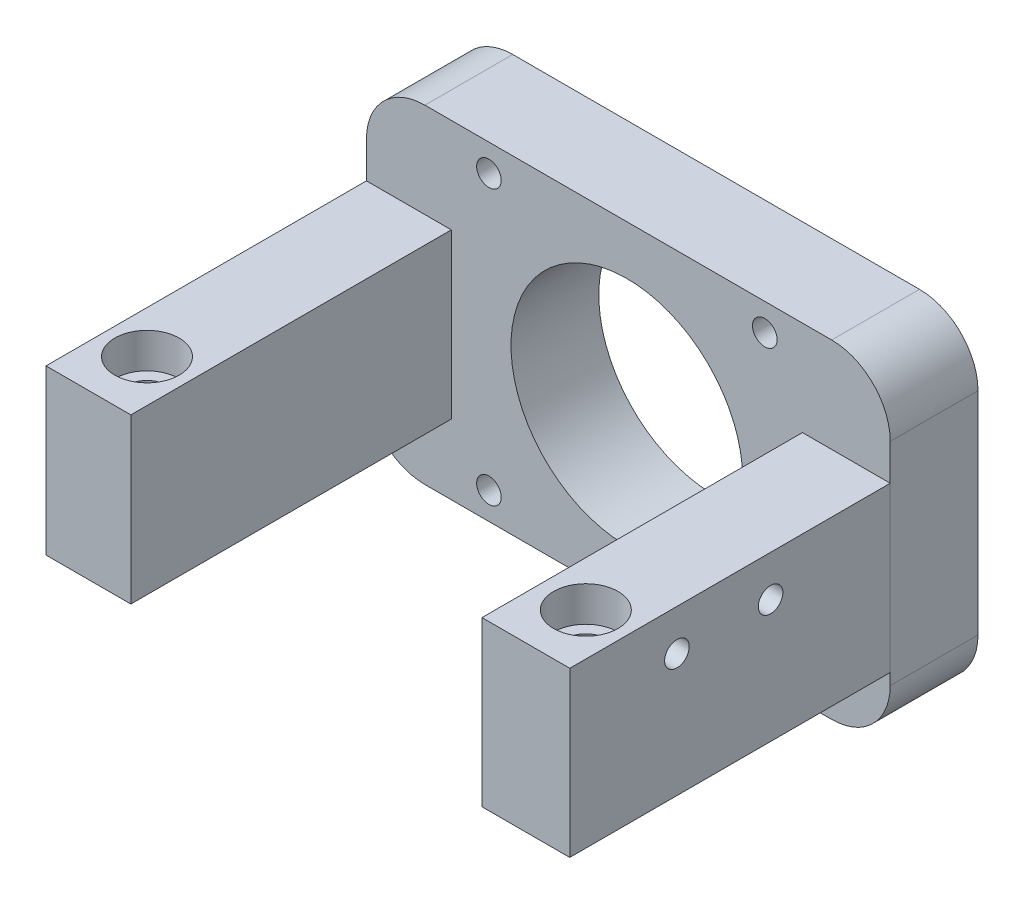
SolidWorks part; units mm, degrees
ref_plane "Default Plane" through (45, -17.95, 15) normal (0, 0, -1) x (-1, 0, 0)
sketch3d "Bounding-Box_Cut-List-Item1"
  line L0 (89.5, 46.15, 0) -> (0, 46.15, 0) construction
  line L1 (0, 46.15, 0) -> (0, -10, 0) construction
  line L2 (0, -10, 0) -> (89.5, -10, 0) construction
  line L3 (89.5, -10, 0) -> (89.5, 46.15, 0) construction
  line L4 (89.5, 46.15, 15) -> (0, 46.15, 15) construction
  line L5 (0, 46.15, 15) -> (0, -10, 15) construction
  line L6 (0, -10, 15) -> (89.5, -10, 15) construction
  line L7 (89.5, -10, 15) -> (89.5, 46.15, 15) construction
  line L8 (89.5, 46.15, 0) -> (89.5, 46.15, 15) construction
  line L9 (0, 46.15, 0) -> (0, 46.15, 15) construction
  line L10 (0, -10, 0) -> (0, -10, 15) construction
  line L11 (89.5, -10, 0) -> (89.5, -10, 15) construction
ref_plane "Default Plane" through (-30, 12, 15) normal (-1, 0, 0) x (0, 0, 1)
sketch3d "Bounding-Box_Cut-List-Item2"
  line L0 (54.7599, -28, 0) -> (0, -28, 0) construction
  line L1 (0, -28, 0) -> (0, 0, 0) construction
  line L2 (0, 0, 0) -> (54.7599, 0, 0) construction
  line L3 (54.7599, 0, 0) -> (54.7599, -28, 0) construction
  line L4 (54.7599, -28, 14.5) -> (0, -28, 14.5) construction
  line L5 (0, -28, 14.5) -> (0, 0, 14.5) construction
  line L6 (0, 0, 14.5) -> (54.7599, 0, 14.5) construction
  line L7 (54.7599, 0, 14.5) -> (54.7599, -28, 14.5) construction
  line L8 (54.7599, -28, 0) -> (54.7599, -28, 14.5) construction
  line L9 (0, -28, 0) -> (0, -28, 14.5) construction
  line L10 (0, 0, 0) -> (0, 0, 14.5) construction
  line L11 (54.7599, 0, 0) -> (54.7599, 0, 14.5) construction
ref_plane "Default Plane" through (45, 12, 15) normal (-1, 0, 0) x (0, 0, 1)
sketch3d "Bounding-Box_Cut-List-Item3"
  line L0 (54.7599, -28, 0) -> (0, -28, 0) construction
  line L1 (0, -28, 0) -> (0, 0, 0) construction
  line L2 (0, 0, 0) -> (54.7599, 0, 0) construction
  line L3 (54.7599, 0, 0) -> (54.7599, -28, 0) construction
  line L4 (54.7599, -28, 15) -> (0, -28, 15) construction
  line L5 (0, -28, 15) -> (0, 0, 15) construction
  line L6 (0, 0, 15) -> (54.7599, 0, 15) construction
  line L7 (54.7599, 0, 15) -> (54.7599, -28, 15) construction
  line L8 (54.7599, -28, 0) -> (54.7599, -28, 15) construction
  line L9 (0, -28, 0) -> (0, -28, 15) construction
  line L10 (0, 0, 0) -> (0, 0, 15) construction
  line L11 (54.7599, 0, 0) -> (54.7599, 0, 15) construction
material "6061 Alloy"
ref_plane "Front Plane" through (0, 0, 0) normal (0, 0, 1) x (1, 0, 0)
ref_plane "Top Plane" through (0, 0, 0) normal (0, 1, 0) x (1, 0, 0)
ref_plane "Right Plane" through (0, 0, 0) normal (1, 0, 0) x (0, 0, -1)
sketch "Sketch1" plane through (0, 0, 0) normal (0, 0, 1) x (1, 0, 0)
  line L0 (11.95, -27.95) -> (-23.7, -27.95) construction
  line L1 (-44.5, 28.2) -> (45, 28.2)
  line L2 (-44.5, 28.2) -> (-44.5, -27.95)
  line L3 (-44.5, -27.95) -> (45, -27.95)
  line L4 (45, 28.2) -> (45, -27.95)
  line L5 (23.7, 28.2) -> (-11.95, 28.2) construction
  line L6 (-29.5, -21.5) -> (-29.5, 10.5) construction
  line L7 (30, -21.5) -> (30, 10.5) construction
  circle A0 centre (0, 0) radius 19.3 construction
  circle A1 centre (0, 0) radius 19.3 construction
  circle A4 centre (0, 0) radius 19.8
  circle A5 centre (0, 0) radius 19.8
  dimension "D2" = 15
  dimension "D3" = 15
  dimension "D1" = 1
extrude "Boss-Extrude1" add sketch "Sketch1" along normal blind 15
sketch "Sketch2" plane through (0, -16, 0) normal (0, 1, 0) x (1, 0, 0)
  line L0 (45, -15) -> (-44.5, -15) construction
  line L1 (-44.5, -15) -> (-30, -15)
  line L2 (-44.5, -15) -> (-44.5, -69.7599)
  line L3 (-44.5, -69.7599) -> (-30, -69.7599)
  line L4 (-30, -15) -> (-30, -69.7599)
  line L5 (30, -69.7599) -> (45, -69.7599)
  line L6 (30, -69.7599) -> (30, -15)
  line L7 (30, -15) -> (45, -15)
  line L8 (45, -69.7599) -> (45, -15)
  line L9 (30, -49.7599) -> (91.1, -49.7599) construction
  dimension "D1" = 20
extrude "Boss-Extrude3" add sketch "Sketch2" along normal offset from surface (28 mm away) 2 separate body
ref_plane "Plane1" through (0.25, 0, 0) normal (1, 0, 0) x (0, 0, -1)
sketch "Sketch3" plane through (0, 0, 0) normal (0, 0, -1) x (-1, 0, 0)
  line L0 (37.0611, -16) -> (37.25, 12) construction
  line L4 (44.5, 12) -> (30, 12)
  line L5 (44.5, -16) -> (44.5, 12)
  line L6 (30, -16) -> (44.5, -16)
  line L7 (30, 12) -> (30, -16)
  line L8 (44.5, 12) -> (30, 12)
  line L9 (44.5, -16) -> (44.5, 12)
  line L10 (30, -16) -> (44.5, -16)
  line L11 (30, 12) -> (30, -16)
  point P6 (37.1555, -2)
  dimension "D1" = 0
hole_wizard "Hole1" positions "3DSketch1" profile "Sketch5" legacy
sketch3d "3DSketch1"
  point P0 (-37.1555, -2, 0)
sketch "Sketch5" plane through (-37.1555, -2, 0) normal (1, 0, 0) x (0, 1, 0)
  line L0 (0, 0) -> (0, 15)
  line L1 (0, 15) -> (3.25, 15)
  line L2 (3.25, 15) -> (3.25, 7)
  line L3 (3.25, 7) -> (5.5, 7)
  line L4 (5.5, 7) -> (5.5, 0)
  line L5 (5.5, 0) -> (0, 0)
  line L6 (0, 110) -> (0, -10) construction
  dimension "Diameter" = 6.5
  dimension "Depth" = 15
  dimension "C-Bore Diameter" = 11
  dimension "C-Bore Depth" = 7
hole_wizard "Tap Drill for M6x1.0 Tap1" positions "3DSketch2" profile "Sketch7" hole size "M6x1.0" standard "ANSI Metric"
sketch3d "3DSketch2"
  point P0 (-37.1555, -2, 0)
sketch "Sketch7" plane through (-37.1555, -2, 0) normal (1, 0, 0) x (0, 1, 0)
  line L0 (0, 0) -> (0, 31.5022)
  line L1 (0, 31.5022) -> (2.5, 30)
  line L2 (2.5, 30) -> (2.5, 0)
  line L5 (2.5, 0) -> (0, 0)
  line L10 (0, 31.5022) -> (-2.5, 30) construction
  line L11 (0, -6.35) -> (0, 107.95) construction
  dimension "Hole Dia." = 5
  dimension "Hole Depth" = 30
  dimension "Drill Angle" = 118
sketch "Sketch8" plane through (0, 12, 0) normal (0, 1, 0) x (1, 0, 0)
  line L0 (-37.2456, -69.7599) -> (-37.2456, -49.7599) construction
  line L4 (-30, -15) -> (-44.5, -15)
  line L5 (-44.5, -15) -> (-44.5, -69.7599)
  line L6 (-44.5, -69.7599) -> (-30, -69.7599)
  line L7 (-30, -69.7599) -> (-30, -15)
  line L8 (-30, -91.7599) -> (-30, -49.7599)
  line L9 (-30, -49.7599) -> (-91.1, -49.7599)
  line L10 (-91.1, -49.7599) -> (-91.1, -399.7599)
  line L11 (-91.1, -399.7599) -> (91.1, -399.7599)
  line L12 (91.1, -399.7599) -> (91.1, -49.7599)
  line L13 (91.1, -49.7599) -> (30, -49.7599)
  line L14 (30, -49.7599) -> (30, -91.7599)
  line L15 (30, -91.7599) -> (-30, -91.7599)
  line L16 (-30, -91.7599) -> (-30, -49.7599)
  line L17 (-30, -49.7599) -> (-91.1, -49.7599)
  line L18 (-91.1, -49.7599) -> (-91.1, -399.7599)
  line L19 (-91.1, -399.7599) -> (91.1, -399.7599)
  line L20 (91.1, -399.7599) -> (91.1, -49.7599)
  line L21 (91.1, -49.7599) -> (30, -49.7599)
  line L22 (30, -49.7599) -> (30, -91.7599)
  line L23 (30, -91.7599) -> (-30, -91.7599)
  line L24 (-30, -15) -> (-44.5, -15)
  line L25 (-44.5, -15) -> (-44.5, -69.7599)
  line L26 (-44.5, -69.7599) -> (-30, -69.7599)
  line L27 (-30, -69.7599) -> (-30, -15)
  point P14 (-37.2456, -59.7599)
  dimension "D1" = 0
  dimension "D2" = 0
hole_wizard "CBORE for M6 SHCS1" positions "3DSketch3" profile "Sketch10" counterbore size "M6" standard "ANSI Metric" end condition up to next
sketch3d "3DSketch3"
  point P0 (-37.2456, 12, 59.7599)
sketch "Sketch10" plane through (-37.2456, 12, 59.7599) normal (1, 0, 0) x (0, 0, 1)
  line L0 (0, 0) -> (0, 28.001)
  line L1 (0, 28.001) -> (3.5, 28.001)
  line L3 (3.5, 28.001) -> (3.5, 6)
  line L4 (3.5, 6) -> (5.5, 6)
  line L5 (5.5, 6) -> (5.5, 0)
  line L7 (5.5, 0) -> (0, 0)
  line L11 (0, -6.35) -> (0, 107.95) construction
  dimension "Thru Hole Dia." = 7
  dimension "Thru Hole Depth" = 28.001
  dimension "C'Bore Dia." = 11
  dimension "C'Bore Depth" = 6
mirror "Mirror1" about plane through (0.25, 0, 0) normal (1, 0, 0) of "CBORE for M6 SHCS1", "Tap Drill for M6x1.0 Tap1", "Hole1"
sketch "Sketch11" plane through (0, 0, 0) normal (0, 0, -1) x (-1, 0, 0)
  line L2 (44.5, 0.125) -> (-45, 0.125) construction
  line L3 (44.5, 28.2) -> (44.5, -27.95) construction
  line L4 (-45, -27.95) -> (-45, 28.2) construction
  circle A2 centre (-23.57, 23.57) radius 2.75 construction
  circle A3 centre (23.57, 23.57) radius 2.75 construction
  circle A4 centre (-23.57, -23.57) radius 2.75 construction
  circle A5 centre (-23.57, 23.57) radius 2.75
  circle A6 centre (23.57, 23.57) radius 2.75
  circle A7 centre (-23.57, -23.57) radius 2.75
  point P16 (23.57, -23.32)
hole_wizard "M5x0.8 Tapped Hole1" positions "3DSketch4" profile "Sketch12" tap size "M5x0.8" standard "ANSI Metric" end condition up to next
sketch3d "3DSketch4"
  point P0 (-23.57, -23.32, 0)
  point P3 (23.57, -23.57, 0)
  point P6 (23.57, 23.57, 0)
  point P9 (-23.57, 23.57, 0)
sketch "Sketch12" plane through (-23.57, -23.32, 0) normal (1, 0, 0) x (0, 1, 0)
  line L0 (0, 0) -> (0, 15)
  line L1 (0, 15) -> (2.1, 15)
  line L2 (2.1, 15) -> (2.1, 0)
  line L5 (2.1, 0) -> (0, 0)
  line L11 (0, -6.35) -> (0, 107.95) construction
  dimension "Thru Tap Drill Dia." = 4.2
  dimension "Thru Tap Drill Depth" = 15
cosmetic thread "Hole Thread1" parameters "D2"=5
cosmetic thread "Hole Thread2" parameters "D2"=5
cosmetic thread "Hole Thread3" parameters "D2"=5
cosmetic thread "Hole Thread4" parameters "D2"=5
fillet "Fillet1" radius 10 4 edges at (45, -27.95, 7.5) (-44.5, -27.95, 7.5) (-44.5, 28.2, 7.5) (45, 28.2, 7.5)
sketch "Sketch13" plane through (45, 0, 0) normal (1, 0, 0) x (0, 0, -1)
  circle A0 centre (-51.4449, 5) radius 5 construction
  circle A1 centre (-35.4449, 5) radius 5 construction
  circle A2 centre (-51.4449, 5) radius 5
  circle A3 centre (-35.4449, 5) radius 5
hole_wizard "Tap Drill for M5x0.8 Tap2" positions "3DSketch5" profile "Sketch15" hole size "M5x0.8" standard "ANSI Metric"
sketch3d "3DSketch5"
  point P0 (45, 5, 35.4449)
  point P3 (45, 5, 51.4449)
sketch "Sketch15" plane through (45, 5, 35.4449) normal (0, 1, 0) x (0, 0, -1)
  line L0 (0, 0) -> (0, 21.2618)
  line L1 (0, 21.2618) -> (2.1, 20)
  line L2 (2.1, 20) -> (2.1, 0)
  line L5 (2.1, 0) -> (0, 0)
  line L10 (0, 21.2618) -> (-2.1, 20) construction
  line L11 (0, -6.35) -> (0, 107.95) construction
  dimension "Hole Dia." = 4.2
  dimension "Hole Depth" = 20
  dimension "Drill Angle" = 118
